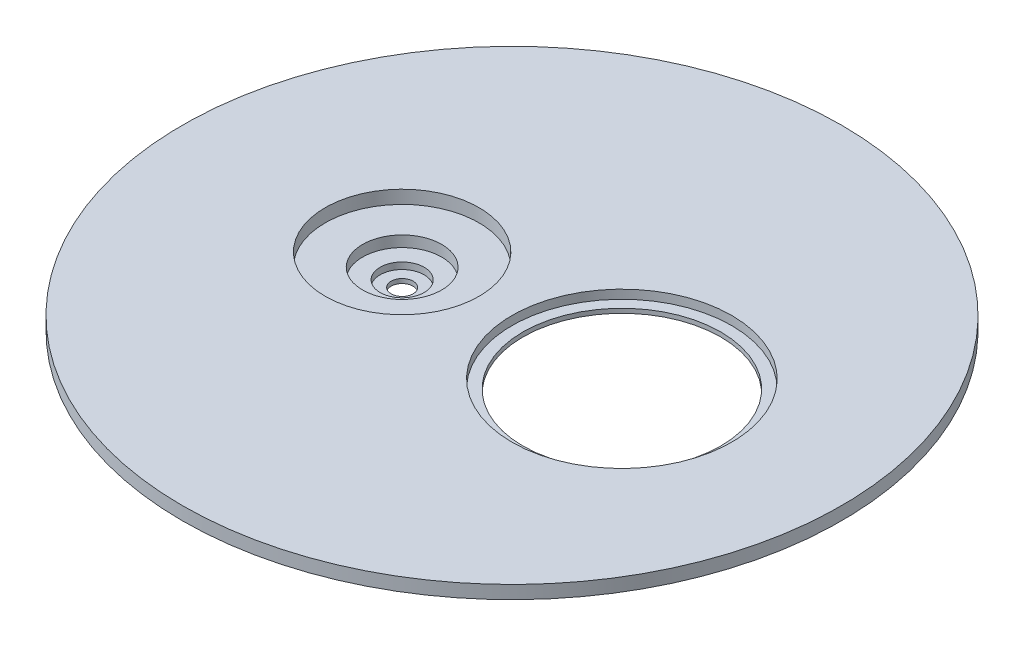
SolidWorks part; units mm, degrees
ref_plane "前视基准面" through (0, 0, 0) normal (0, 0, 1) x (1, 0, 0)
ref_plane "上视基准面" through (0, 0, 0) normal (0, 1, 0) x (1, 0, 0)
ref_plane "右视基准面" through (0, 0, 0) normal (1, 0, 0) x (0, 0, -1)
sketch "草图1" plane through (0, 0, 0) normal (0, 1, 0) x (1, 0, 0)
  circle A0 centre (0, 0) radius 75
  dimension "D1" = 150
extrude "凸台-拉伸1" add sketch "草图1" along normal blind 3
sketch "草图2" plane through (0, 3, 0) normal (0, 1, 0) x (1, 0, 0)
  line L0 (0, 0) -> (-25, 0)
  line L1 (0, 0) -> (25, 0)
  circle A0 centre (-25, 0) radius 17.5
  circle A1 centre (25, 0) radius 25
  dimension "D3" = 35
  dimension "D4" = 50
  dimension "D1" = 25
  dimension "D2" = 25
extrude "切除-拉伸1" cut sketch "草图2" against normal blind 2 contours A1 | A0
sketch "草图3" plane through (0, 0, 0) normal (0, -1, 0) x (1, 0, 0)
  circle A1 centre (25, 0) radius 22.5
  dimension "D2" = 45
extrude "切除-拉伸2" cut sketch "草图3" against normal blind 2
sketch "草图4" plane through (0, 0, 0) normal (0, -1, 0) x (1, 0, 0)
  line L0 (0, 0) -> (0, 76.8141)
sketch "草图6" plane through (0, 3, 0) normal (0, 1, 0) x (1, 0, 0)
  line L0 (0, 37.5) -> (0, -37.5)
  circle A0 centre (0, 37.5) radius 2.5
  circle A1 centre (0, -37.5) radius 2.5
  point P4 (0, 0)
  dimension "D2" = 5
  dimension "D3" = 5
  dimension "D1" = 75
extrude "切除-拉伸4" [suppressed] cut sketch "草图6" against normal blind 2 contours A0 | A1
sketch "草图12" plane through (0, 1, 0) normal (0, 1, 0) x (1, 0, 0)
  circle A0 centre (-25, 0) radius 17.5
  dimension "D1" = 35
extrude "切除-拉伸7" cut sketch "草图12" against normal blind 1
sketch "草图15" plane through (0, 0, 0) normal (0, -1, 0) x (1, 0, 0)
  circle A0 centre (-25, 0) radius 18.5
  circle A1 centre (-25, 0) radius 9
  dimension "D1" = 37
  dimension "D2" = 18
extrude "凸台-拉伸6" add sketch "草图15" along normal blind 2.5
sketch "草图16" plane through (0, -2.5, 0) normal (0, -1, 0) x (1, 0, 0)
  circle A0 centre (-25, 0) radius 10
  circle A1 centre (-25, 0) radius 2.5
  dimension "D1" = 20
  dimension "D2" = 5
extrude "凸台-拉伸7" add sketch "草图16" along normal blind 2.5
sketch "草图17" plane through (0, -2.5, 0) normal (0, 1, 0) x (1, 0, 0)
  circle A0 centre (-25, 0) radius 5
  dimension "D1" = 10
extrude "切除-拉伸9" cut sketch "草图17" against normal blind 1.5
